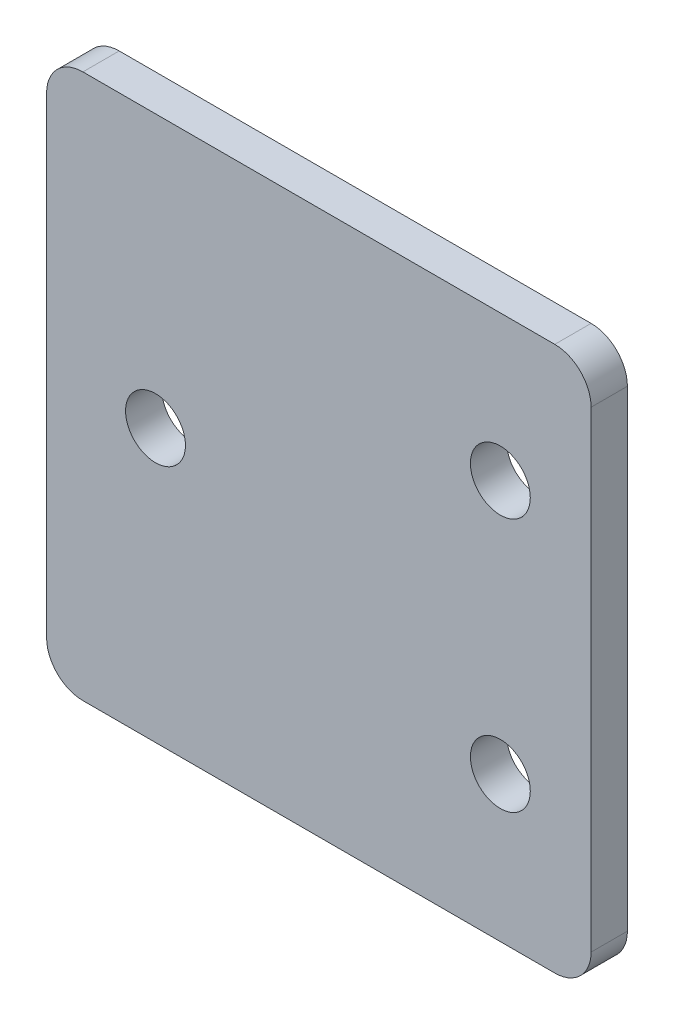
SolidWorks part; units mm, degrees
ref_plane "Front Plane" through (0, 0, 0) normal (0, 0, 1) x (1, 0, 0)
ref_plane "Top Plane" through (0, 0, 0) normal (0, 1, 0) x (1, 0, 0)
ref_plane "Right Plane" through (0, 0, 0) normal (1, 0, 0) x (0, 0, -1)
sketch "Sketch1" plane through (0, 0, 0) normal (0, 0, 1) x (1, 0, 0)
  line L1 (-15, -15) -> (15, -15)
  line L2 (-15, -15) -> (-15, 15)
  line L3 (-15, 15) -> (15, 15)
  line L4 (15, -15) -> (15, 15)
  line L5 (-15, -15) -> (15, 15) construction
  line L6 (-15, 15) -> (15, -15) construction
  point P0 (0, 0)
  dimension "D1" = 30
  dimension "D2" = 30
extrude "Boss-Extrude1" add sketch "Sketch1" along normal blind 2
fillet "Fillet1" radius 2 4 edges at (15, -15, 1) (15, 15, 1) (-15, -15, 1) (-15, 15, 1)
sketch "Sketch2" plane through (0, 0, 2) normal (0, 0, 1) x (1, 0, 0)
  line L0 (-15, 13) -> (-15, -13) construction
  line L1 (13, 15) -> (-13, 15) construction
  point P0 (-9, 0)
  point P2 (10, 7)
  point P3 (10, -7)
  dimension "D1" = 6
  dimension "D2" = 19
  dimension "D3" = 14
  dimension "D4" = 8
hole_wizard "Ø3.0mm Dowel Hole1" positions "3DSketch1" profile "Sketch3" hole size "Ø3.0" standard "ISO" end condition through all
sketch3d "3DSketch1"
  point P0 (-9, 0, 2)
  point P3 (10, 7, 2)
  point P6 (10, -7, 2)
sketch "Sketch3" plane through (-9, 0, 2) normal (1, 0, 0) x (0, -1, 0)
  line L0 (0, 0) -> (0, 2)
  line L1 (0, 2) -> (1.65, 2)
  line L2 (1.65, 2) -> (1.65, 0)
  line L5 (1.65, 0) -> (0, 0)
  line L11 (0, -6.35) -> (0, 107.95) construction
  dimension "Thru Hole Dia." = 3.3
  dimension "Thru Hole Depth" = 2
